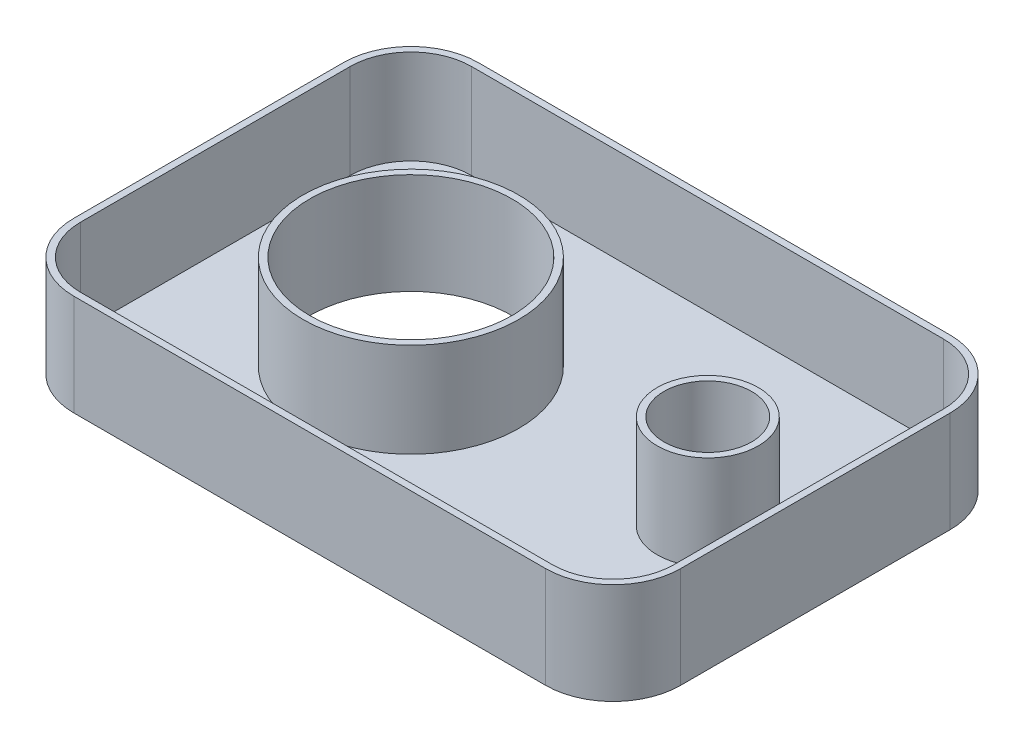
SolidWorks part; units mm, degrees
ref_plane "前视基准面" through (0, 0, 0) normal (0, 0, 1) x (1, 0, 0)
ref_plane "上视基准面" through (0, 0, 0) normal (0, 1, 0) x (1, 0, 0)
ref_plane "右视基准面" through (0, 0, 0) normal (1, 0, 0) x (0, 0, -1)
other "Configuration Table"
sketch "Sketch1" plane through (0, 0, 0) normal (0, 1, 0) x (1, 0, 0)
  line L1 (0, 0) -> (180, 0)
  line L2 (0, 0) -> (0, -120)
  line L3 (0, -120) -> (180, -120)
  line L4 (180, 0) -> (180, -120)
  dimension "D1" = 120
  dimension "D2" = 180
extrude "Boss-Extrude1" add sketch "Sketch1" along normal blind 30
sketch "Sketch4" plane through (0, 30, 0) normal (0, 1, 0) x (1, 0, 0)
  line L0 (0, 0) -> (0, -120) construction
  line L2 (0, -120) -> (180, -120) construction
  circle A0 centre (60, -60) radius 30
  circle A1 centre (145, -56.9264) radius 13
  dimension "D1" = 60
  dimension "D4" = 26
  dimension "D2" = 60
  dimension "D3" = 60
  dimension "D5" = 85
extrude "Cut-Extrude1" cut sketch "Sketch4" against normal through all
fillet "Fillet1" radius 20 4 edges at (0, 15, 120) (0, 15, 0) (180, 15, 0) (180, 15, 120)
shell "Shell2" thickness 2
